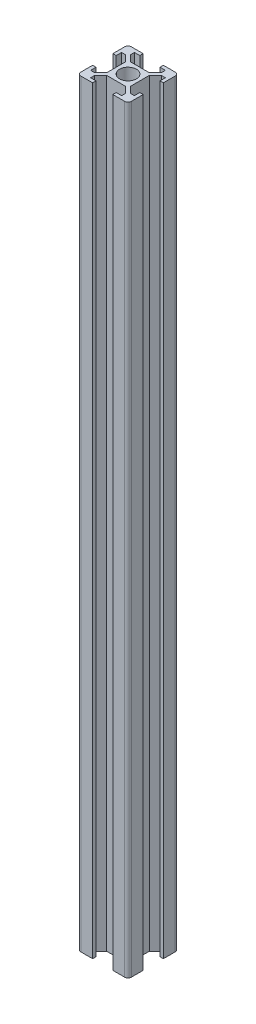
SolidWorks part; units mm, degrees
ref_plane "Front Plane" through (0, 0, 0) normal (0, 0, 1) x (1, 0, 0)
ref_plane "Top Plane" through (0, 0, 0) normal (0, 1, 0) x (1, 0, 0)
ref_plane "Right Plane" through (0, 0, 0) normal (1, 0, 0) x (0, 0, -1)
sketch "Sketch1" plane through (0, 0, 0) normal (0, 1, 0) x (1, 0, 0)
  line L0 (-7.5, -3) -> (-7.5, -6.5)
  line L5 (-6.5, -7.5) -> (-3, -7.5)
  line L6 (-7.5, -3) -> (-6.5, -3)
  line L7 (-3, -7.5) -> (-3, -6.5)
  line L8 (-6.5, -3) -> (-6.5, -4.6)
  line L9 (-3, -6.5) -> (-4.6, -6.5)
  line L10 (-6.5, -4.6) -> (-5.3071, -4.6)
  line L11 (-4.6, -6.5) -> (-4.6, -5.3071)
  line L13 (-3.5071, 0) -> (-3.5071, -2.8)
  line L14 (-3.5071, -2.8) -> (-5.3071, -4.6)
  line L16 (0, -3.5071) -> (-2.8, -3.5071)
  line L17 (-2.8, -3.5071) -> (-4.6, -5.3071)
  line L18 (-3.5071, 2.8) -> (-5.3071, 4.6)
  line L19 (-6.5, 4.6) -> (-5.3071, 4.6)
  line L20 (-6.5, 3) -> (-6.5, 4.6)
  line L21 (-7.5, 3) -> (-6.5, 3)
  line L22 (-7.5, 6.5) -> (-7.5, 3)
  line L23 (-3, 7.5) -> (-6.5, 7.5)
  line L24 (-3, 7.5) -> (-3, 6.5)
  line L25 (-3, 6.5) -> (-4.6, 6.5)
  line L26 (-4.6, 6.5) -> (-4.6, 5.3071)
  line L27 (-2.8, 3.5071) -> (-4.6, 5.3071)
  line L28 (0, 3.5071) -> (-2.8, 3.5071)
  line L31 (-3.5071, 0) -> (-3.5071, 2.8)
  line L32 (2.8, 3.5071) -> (4.6, 5.3071)
  line L33 (4.6, 6.5) -> (4.6, 5.3071)
  line L34 (3, 6.5) -> (4.6, 6.5)
  line L35 (3, 7.5) -> (3, 6.5)
  line L36 (6.5, 7.5) -> (3, 7.5)
  line L37 (7.5, 3) -> (7.5, 6.5)
  line L38 (7.5, 3) -> (6.5, 3)
  line L39 (6.5, 3) -> (6.5, 4.6)
  line L40 (6.5, 4.6) -> (5.3071, 4.6)
  line L41 (3.5071, 2.8) -> (5.3071, 4.6)
  line L42 (3.5071, 0) -> (3.5071, 2.8)
  line L45 (0, 3.5071) -> (2.8, 3.5071)
  line L46 (3.5071, -2.8) -> (5.3071, -4.6)
  line L47 (6.5, -4.6) -> (5.3071, -4.6)
  line L48 (6.5, -3) -> (6.5, -4.6)
  line L49 (7.5, -3) -> (6.5, -3)
  line L50 (7.5, -6.5) -> (7.5, -3)
  line L51 (3, -7.5) -> (6.5, -7.5)
  line L52 (3, -7.5) -> (3, -6.5)
  line L53 (3, -6.5) -> (4.6, -6.5)
  line L54 (4.6, -6.5) -> (4.6, -5.3071)
  line L55 (2.8, -3.5071) -> (4.6, -5.3071)
  line L56 (0, -3.5071) -> (2.8, -3.5071)
  line L59 (3.5071, 0) -> (3.5071, -2.8)
  arc A1 (-6.5, -7.5) -> (-7.5, -6.5) centre (-6.5, -6.5) cw
  arc A2 (-2.5, 0) -> (0, -2.5) centre (0, 0) ccw
  arc A3 (-7.5, 6.5) -> (-6.5, 7.5) centre (-6.5, 6.5) cw
  arc A4 (0, 2.5) -> (-2.5, 0) centre (0, 0) ccw
  arc A5 (6.5, 7.5) -> (7.5, 6.5) centre (6.5, 6.5) cw
  arc A6 (2.5, 0) -> (0, 2.5) centre (0, 0) ccw
  arc A7 (7.5, -6.5) -> (6.5, -7.5) centre (6.5, -6.5) cw
  arc A8 (0, -2.5) -> (2.5, 0) centre (0, 0) ccw
  point P8 (-7.5, -3)
  point P9 (-3, -7.5)
  point P75 (0, 0)
  dimension "D1" = 1
  dimension "D9" = 2.5
  dimension "D2" = 3
  dimension "D3" = 7.5
  dimension "D4" = 3
  dimension "D5" = 1
  dimension "D6" = 1
  dimension "D7" = 1.6
  dimension "D8" = 2.8
  dimension "D10" = 1
  dimension "D11" = 4
extrude "Boss-Extrude1" add sketch "Sketch1" along normal blind 225
